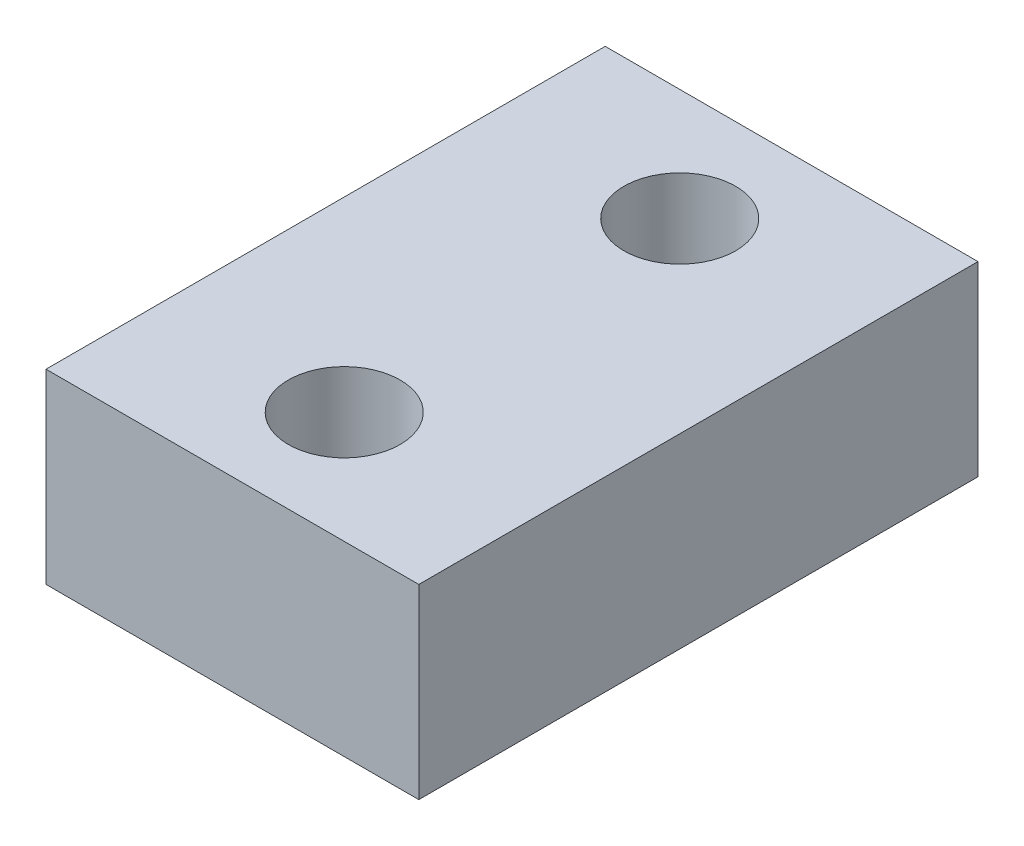
SolidWorks part; units mm, degrees
ref_plane "Piano frontale" through (0, 0, 0) normal (0, 0, 1) x (1, 0, 0)
ref_plane "Piano superiore" through (0, 0, 0) normal (0, 1, 0) x (1, 0, 0)
ref_plane "Piano destro" through (0, 0, 0) normal (1, 0, 0) x (0, 0, -1)
sketch "Schizzo1" plane through (0, 0, 0) normal (0, 0, 1) x (1, 0, 0)
  line L0 (0, 0) -> (-10, 0)
  line L1 (-10, 0) -> (-10, 5)
  line L2 (-10, 5) -> (0, 5)
  line L3 (0, 5) -> (0, 0)
  dimension "D1" = 10
  dimension "D2" = 5
extrude "Estrusione-Estrusione1" add sketch "Schizzo1" along normal blind 15
sketch "Schizzo2" plane through (0, 0, 0) normal (0, -1, 0) x (-1, 0, 0)
  line L0 (10, 0) -> (0, 0) construction
  line L1 (5, -15) -> (5, 3.3709) construction
  line L2 (10, -15) -> (0, -15) construction
  circle A0 centre (5, -12) radius 1.5
  circle A1 centre (5, -3) radius 1.5
  dimension "D3" = 3
  dimension "D1" = 9
  dimension "D2" = 3
extrude "Taglio-Estrusione1" cut sketch "Schizzo2" against normal through all
